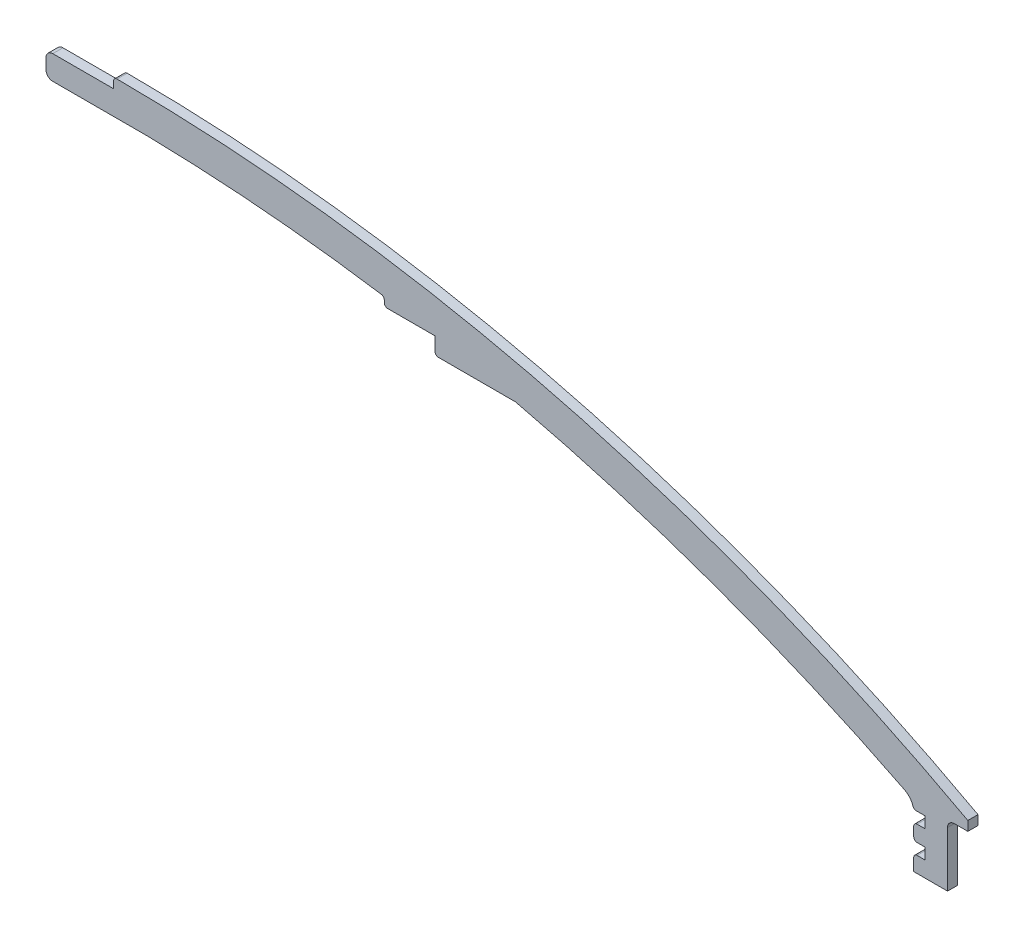
SolidWorks part; units mm, degrees
ref_plane "Front Plane" through (0, 0, 0) normal (0, 0, 1) x (1, 0, 0)
ref_plane "Top Plane" through (0, 0, 0) normal (0, 1, 0) x (1, 0, 0)
ref_plane "Right Plane" through (0, 0, 0) normal (1, 0, 0) x (0, 0, -1)
sketch "Sketch1" plane through (0, 0, 0) normal (0, 0, 1) x (1, 0, 0)
  line L0 (-45, 0) -> (45, 0) construction
  line L1 (300, -65.3534) -> (300, -85.3534)
  line L2 (-45, -150.7069) -> (45, -150.7069) construction
  line L3 (-45, 0) -> (-45, -150.7069) construction
  line L4 (45, 0) -> (45, -150.7069) construction
  line L5 (0, 0) -> (0, -150.7069)
  line L6 (45, 0) -> (0, 0)
  line L7 (0, -150.7069) -> (45, -150.7069)
  arc A0 (45, 0) -> (300, -65.3534) centre (45, -530.1639) cw
  arc A1 (-28.1177, 0) -> (35.3823, 0) centre (3.6323, -0.0236) cw construction
  arc A2 (45, -150.7069) -> (300, -85.3534) centre (45, 379.457) ccw
  point P4 (0, 0)
  dimension "D2" = 300
  dimension "D3" = 31.75
  dimension "D5" = 150.7069
  dimension "D1" = 90
  dimension "D4" = 20
sketch "Sketch2" plane through (0, 0, 0) normal (0, 0, 1) x (1, 0, 0)
  line L0 (299.5, -67.3534) -> (293.5, -67.3534)
  line L1 (291.5, -69.3534) -> (291.5, -85.6495)
  line L2 (54.9033, -10.5962) -> (27, -10.5962)
  line L3 (25, -8.5962) -> (25, -5.5)
  line L4 (300, -65.3534) -> (300, -85.3534) construction
  line L5 (300, -65.3534) -> (300, -85.3534) construction
  line L6 (299.5, -65.6495) -> (299.5, -67.3534)
  line L7 (291.5, -85.6495) -> (281.5, -85.6495)
  line L8 (45, -1.5009) -> (45, -3.5)
  line L9 (45, 0) -> (45, -150.7069) construction
  line L10 (45, -3.5) -> (27, -3.5)
  line L11 (281.5, -85.6495) -> (281.5, -70.5046)
  line L12 (45, -0.5) -> (0.5, -0.5)
  line L13 (0.5, -0.5) -> (0.5, -150.2069)
  line L14 (0.5, -150.2069) -> (45, -150.2069)
  line L15 (299.5, -85.0574) -> (299.5, -65.6495)
  line L20 (55, -13.5) -> (25, -13.5) construction
  line L21 (55, -10.5962) -> (55, -13.5) construction
  line L22 (140, -19.2573) -> (140, -23.2573)
  line L23 (140, -19.2573) -> (126, -19.2573)
  line L24 (125, -18.2573) -> (125, -17.5517)
  line L25 (141, -24.2573) -> (163.7816, -24.2573)
  line L26 (0, 0) -> (0, -150.7069) construction
  line L27 (45, -3.5) -> (25, -3.5) construction
  line L28 (45, -0.5) -> (45, -3.5) construction
  arc A0 (278.749, -66.039) -> (163.7816, -24.2573) centre (45, -530.1639) ccw
  arc A1 (294.6951, -74.4195) -> (55, -10.5962) centre (45, -530.1639) ccw construction
  arc A2 (55.0976, -10.5981) -> (54.9033, -10.5962) centre (54.9033, -20.5962) ccw
  arc A3 (281.5, -70.5046) -> (278.749, -66.039) centre (276.5, -70.5046) ccw
  arc A4 (293.5, -67.3534) -> (291.5, -69.3534) centre (293.5, -69.3534) ccw
  arc A5 (124.1523, -16.5634) -> (55.0976, -10.5981) centre (45, -530.1639) ccw
  arc A6 (45, -150.2069) -> (299.5, -85.0574) centre (45, 379.457) ccw
  arc A7 (299.5, -65.6495) -> (45, -0.5) centre (45, -530.1639) ccw
  arc A9 (299.5, -65.6495) -> (46.0019, -0.5009) centre (45, -530.1639) ccw
  arc A10 (125, -16.6947) -> (163.7816, -24.2573) centre (45, -530.1639) cw construction
  arc A11 (140, -23.2573) -> (141, -24.2573) centre (141, -23.2573) ccw
  arc A12 (126, -19.2573) -> (125, -18.2573) centre (126, -18.2573) cw
  arc A13 (125, -17.5517) -> (124.1523, -16.5634) centre (124, -17.5517) ccw
  arc A14 (27, -10.5962) -> (25, -8.5962) centre (27, -8.5962) cw
  arc A15 (27, -3.5) -> (25, -5.5) centre (27, -5.5) ccw
  arc A16 (299.5, -65.6495) -> (45, -0.5) centre (45, -530.1639) ccw construction
  arc A17 (45, -1.5009) -> (46.0019, -0.5009) centre (46, -1.5009) cw
  point P26 (300, -75.3534)
  point P33 (291.5, -67.3534)
  point P43 (140, -24.2573)
  point P48 (125, -19.2573)
  point P57 (25, -3.5)
  dimension "D5" = 10
  dimension "D10" = 5
  dimension "D11" = 2
  dimension "D16" = 1
  dimension "D17" = 2
  dimension "D18" = 1
  dimension "D2" = 20
  dimension "D3" = 3
  dimension "D6" = 7.0962
  dimension "D7" = 8
  dimension "D8" = 8
  dimension "D9" = 10
  dimension "D12" = 20
  dimension "D13" = 15
  dimension "D14" = 5
  dimension "D15" = 140
  dimension "D1" = 0.5
  dimension "D4" = 10
extrude "Boss-Extrude1" add sketch "Sketch2" along normal mid plane 3
sketch "Sketch3" plane through (0, 0, 1.5) normal (0, 0, 1) x (1, 0, 0)
  line L0 (300, -75.3534) -> (270.8122, -75.3534) construction
  line L1 (300, -65.3534) -> (300, -85.3534) construction
  line L3 (279.9796, -69.7034) -> (284.8, -69.7034)
  line L4 (279.9796, -69.7034) -> (279.9796, -73.0034)
  line L5 (279.9796, -73.0034) -> (284.8, -73.0034)
  line L6 (284.8, -69.7034) -> (284.8, -73.0034)
  line L7 (281.5, -70.5046) -> (281.5, -85.6495) construction
  line L8 (284.8, -81.0034) -> (284.8, -77.7034)
  line L9 (279.9796, -77.7034) -> (284.8, -77.7034)
  line L10 (279.9796, -81.0034) -> (279.9796, -77.7034)
  line L11 (279.9796, -81.0034) -> (284.8, -81.0034)
  point P10 (284.8, -71.3534)
  dimension "D1" = 3.3
  dimension "D2" = 4
  dimension "D3" = 3.3
extrude "Cut-Extrude1" cut sketch "Sketch3" against normal blind 10
fillet "Fillet1" radius 1 4 edges at (281.5, -81.0034, 0) (281.5, -77.7034, 0) (281.5, -73.0034, 0) (281.4354, -69.7034, 0)
sketch "Sketch4" plane through (0, 0, 1.5) normal (0, 0, 1) x (1, 0, 0)
  line L0 (299.5, -67.3534) -> (299.5, -65.6495) construction
  line L1 (297.5, -62.5957) -> (299.5, -62.5957)
  line L2 (297.5, -62.5957) -> (297.5, -69.6147)
  line L3 (297.5, -69.6147) -> (299.5, -69.6147)
  line L4 (299.5, -62.5957) -> (299.5, -69.6147)
  dimension "D1" = 2
extrude "Cut-Extrude2" cut sketch "Sketch4" against normal blind 10
